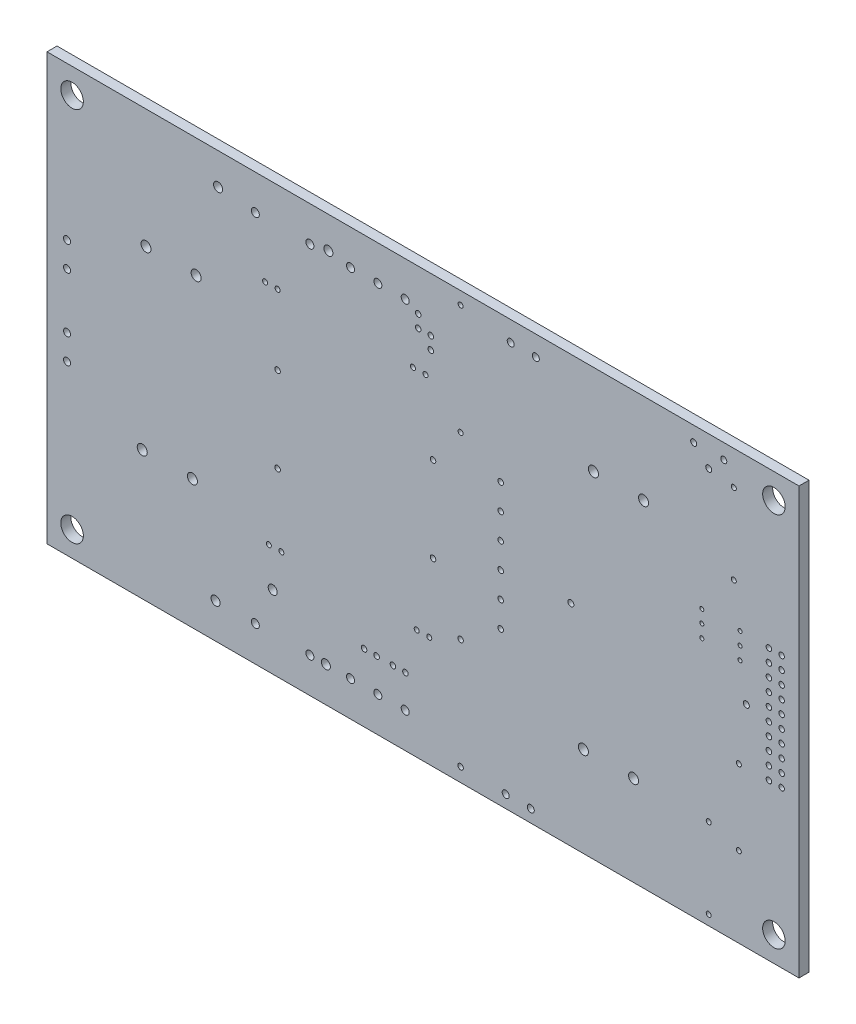
SolidWorks part; units mm, degrees
ref_plane "Спереди" through (0, 0, 0) normal (0, 0, 1) x (1, 0, 0)
ref_plane "Сверху" through (0, 0, 0) normal (0, 1, 0) x (1, 0, 0)
ref_plane "Справа" through (0, 0, 0) normal (1, 0, 0) x (0, 0, -1)
sketch "Эскиз1" plane through (0, 0, 0) normal (0, 0, 1) x (1, 0, 0)
  line L0 (-22.6071, 0) -> (23.7373, 0) construction
  line L1 (-75, -42.5) -> (75, -42.5)
  line L2 (-75, -42.5) -> (-75, 42.5)
  line L3 (-75, 42.5) -> (75, 42.5)
  line L4 (75, -42.5) -> (75, 42.5)
  line L5 (0, 0) -> (0, 31.6453) construction
  circle A0 centre (-70, -37.5) radius 2.25
  circle A1 centre (70, -37.5) radius 2.25
  circle A2 centre (70, 37.5) radius 2.25
  circle A3 centre (-70, 37.5) radius 2.25
  dimension "D3" = 4.5
  dimension "D1" = 150
  dimension "D2" = 85
  dimension "D4" = 5
  dimension "D5" = 5
extrude "Вытянуть1" add sketch "Эскиз1" along normal blind 2
sketch "Эскиз2" plane through (0, 0, 2) normal (0, 0, 1) x (1, 0, 0)
  line L0 (-75, 42.5) -> (-75, -42.5) construction
  line L1 (-75, -42.5) -> (75, -42.5) construction
  line L2 (-33.45, 35.5) -> (-22.55, 35.5) construction
  line L3 (-14.45, -35.5) -> (-3.55, -35.5) construction
  line L4 (69, 11.5) -> (71.54, 11.5) construction
  line L5 (15.5, -11.95) -> (48.2663, -11.95) construction
  line L6 (15.5, -11.95) -> (27.9466, 0.4966) construction
  line L14 (63, -26.5) -> (63, -11.5) construction
  line L15 (-14.45, 35.5) -> (-3.55, 35.5) construction
  line L16 (-33.45, -35.5) -> (-22.55, -35.5) construction
  line L18 (15.5, -22.58) -> (15.5, -11.95) construction
  circle A0 centre (69, 11.5) radius 0.55
  circle A1 centre (71.54, 11.5) radius 0.55
  circle A2 centre (69, 8.96) radius 0.55
  circle A3 centre (71.54, 8.96) radius 0.55
  circle A4 centre (69, 6.42) radius 0.55
  circle A5 centre (71.54, 6.42) radius 0.55
  circle A6 centre (69, 3.88) radius 0.55
  circle A7 centre (71.54, 3.88) radius 0.55
  circle A8 centre (69, 1.34) radius 0.55
  circle A9 centre (71.54, 1.34) radius 0.55
  circle A10 centre (69, -1.2) radius 0.55
  circle A11 centre (71.54, -1.2) radius 0.55
  circle A12 centre (69, -3.74) radius 0.55
  circle A13 centre (71.54, -3.74) radius 0.55
  circle A14 centre (69, -6.28) radius 0.55
  circle A15 centre (71.54, -6.28) radius 0.55
  circle A16 centre (69, -8.82) radius 0.55
  circle A17 centre (71.54, -8.82) radius 0.55
  circle A18 centre (69, -11.36) radius 0.55
  circle A19 centre (71.54, -11.36) radius 0.55
  circle A20 centre (63, -26.5) radius 0.5
  circle A21 centre (63, -11.5) radius 0.5
  circle A22 centre (-14.45, 35.5) radius 0.8
  circle A23 centre (-9, 35.5) radius 0.8
  circle A24 centre (-3.55, 35.5) radius 0.8
  circle A25 centre (-33.45, 35.5) radius 0.8
  circle A27 centre (-22.55, 35.5) radius 0.8
  circle A28 centre (-33.45, -35.5) radius 0.8
  circle A30 centre (-22.55, -35.5) radius 0.8
  circle A31 centre (-14.45, -35.5) radius 0.8
  circle A32 centre (-9, -35.5) radius 0.8
  circle A33 centre (-3.55, -35.5) radius 0.8
  circle A37 centre (15.5, 13.45) radius 0.55
  circle A38 centre (15.5, 8.37) radius 0.55
  circle A39 centre (15.5, -1.79) radius 0.55
  circle A40 centre (15.5, 3.29) radius 0.55
  circle A41 centre (15.5, -6.87) radius 0.55
  circle A45 centre (15.5, -11.95) radius 0.55
  dimension "D3" = 1.1
  dimension "D4" = 2.54
  dimension "D7" = 1
  dimension "D8" = 138
  dimension "D9" = 60.55
  dimension "D10" = 10.9
  dimension "D11" = 1.1
  dimension "D12" = 78
  dimension "D13" = 1.6
  dimension "D19" = 1.6
  dimension "D20" = 5.45
  dimension "D14" = 10.9
  dimension "D26" = 10.9
  dimension "D30" = 5.08
  dimension "D32" = 30.55
  dimension "D6" = 15
  dimension "D33" = 5.08
  dimension "D34" = 5.08
  dimension "D36" = 5.08
  dimension "D42" = 1.6
  dimension "D24" = 54
  dimension "D35" = 5.08
  dimension "D1" = 144
  dimension "D5" = 16
  dimension "D15" = 41.55
  dimension "D16" = 78
  dimension "D17" = 7
  dimension "D18" = 7
  dimension "D21" = 41.55
  dimension "D22" = 60.55
  dimension "D25" = 45
  dimension "D31" = 90.5
extrude "Вырез-Вытянуть1" cut sketch "Эскиз2" against normal blind 2
sketch "Эскиз3" plane through (0, 0, 2) normal (0, 0, 1) x (1, 0, 0)
  line L0 (-75, -42.5) -> (75, -42.5) construction
  line L1 (-75, 42.5) -> (-75, -42.5) construction
  line L2 (-55.25, 18.75) -> (-45.25, 18.75) construction
  line L6 (16.5, -40) -> (21.5, -40) construction
  line L7 (-71, 7) -> (-71, 12) construction
  line L8 (-71, -9) -> (-71, -4) construction
  line L9 (-75, -42.5) -> (75, -42.5) construction
  line L12 (57, -40.5) -> (57, -24.5) construction
  line L14 (47.25, 45) -> (47.25, 55) construction
  line L16 (34, 24.5) -> (44, 24.5) construction
  line L17 (32, -24.5) -> (42, -24.5) construction
  line L18 (-56, -16.75) -> (-46, -16.75) construction
  line L19 (62, 19.75) -> (62, 35.75) construction
  line L20 (63.24, 11.58) -> (63.24, 6.5) construction
  line L21 (55.62, 6.5) -> (55.62, 12.7862) construction
  line L22 (55.62, 6.5) -> (63.24, 6.5) construction
  line L23 (54, 39.5) -> (60, 39.5) construction
  line L24 (17.5, 38.5) -> (22.5, 38.5) construction
  line L25 (29.5, -0.5) -> (64.5, -0.5) construction
  circle A0 centre (-55.25, 18.75) radius 1
  circle A1 centre (-45.25, 18.75) radius 1
  circle A2 centre (-56, -16.75) radius 1
  circle A3 centre (-46, -16.75) radius 1
  circle A4 centre (54, 39.5) radius 0.6
  circle A5 centre (60, 39.5) radius 0.6
  circle A10 centre (16.5, -40) radius 0.7
  circle A12 centre (21.5, -40) radius 0.7
  circle A13 centre (-71, 7) radius 0.7
  circle A14 centre (-71, 12) radius 0.7
  circle A15 centre (-71, -9) radius 0.7
  circle A16 centre (-71, -4) radius 0.7
  circle A20 centre (57, -40.5) radius 0.5
  circle A21 centre (57, -24.5) radius 0.5
  circle A28 centre (34, 24.5) radius 1
  circle A29 centre (44, 24.5) radius 1
  circle A30 centre (32, -24.5) radius 1
  circle A31 centre (42, -24.5) radius 1
  circle A34 centre (57, 36.5) radius 0.6
  circle A35 centre (17.5, 38.5) radius 0.7
  circle A36 centre (62, 19.75) radius 0.5
  circle A37 centre (62, 35.75) radius 0.5
  circle A38 centre (63.24, 11.58) radius 0.4
  circle A39 centre (63.24, 6.5) radius 0.4
  circle A40 centre (55.62, 9.04) radius 0.4
  circle A41 centre (63.24, 9.04) radius 0.4
  circle A42 centre (55.62, 6.5) radius 0.4
  circle A43 centre (55.62, 11.58) radius 0.4
  circle A44 centre (22.5, 38.5) radius 0.7
  circle A45 centre (64.5, -0.5) radius 0.6
  circle A46 centre (29.5, -0.5) radius 0.6
  dimension "D16" = 91.5
  dimension "D17" = 5
  dimension "D18" = 49.5
  dimension "D22" = 1.2
  dimension "D23" = 1.2
  dimension "D28" = 1
  dimension "D44" = 10
  dimension "D14" = 5
  dimension "D15" = 2.5
  dimension "D30" = 16
  dimension "D35" = 10
  dimension "D20" = 1.4
  dimension "D50" = 1.4
  dimension "D56" = 19.75
  dimension "D58" = 25.75
  dimension "D59" = 16
  dimension "D63" = 7.62
  dimension "D64" = 2.54
  dimension "D65" = 5.08
  dimension "D67" = 130.62
  dimension "D70" = 6
  dimension "D72" = 6
  dimension "D76" = 5
  dimension "D77" = 1.4
  dimension "D78" = 35
  dimension "D19" = 4
  dimension "D21" = 5
  dimension "D29" = 2
  dimension "D31" = 132
  dimension "D34" = 10
  dimension "D38" = 122.25
  dimension "D45" = 67
  dimension "D46" = 109
  dimension "D47" = 10
  dimension "D48" = 18
  dimension "D49" = 107
  dimension "D51" = 4
  dimension "D52" = 33.5
  dimension "D57" = 61.25
  dimension "D60" = 137
  dimension "D61" = 62.25
  dimension "D62" = 5.08
  dimension "D66" = 49
  dimension "D68" = 19
  dimension "D69" = 3
  dimension "D71" = 82
  dimension "D73" = 129
  dimension "D74" = 81
  dimension "D75" = 92.5
  dimension "D79" = 42
  dimension "D80" = 104.5
extrude "Вырез-Вытянуть2" cut sketch "Эскиз3" against normal blind 10
sketch "Эскиз4" plane through (0, 0, 2) normal (0, 0, 1) x (1, 0, 0)
  line L0 (-41.37, -35.5) -> (-19.37, -35.5) construction
  line L1 (-75, 42.5) -> (-75, -42.5) construction
  line L2 (-75, -42.5) -> (75, -42.5) construction
  line L3 (-40.87, 36.2) -> (-18.87, 36.2) construction
  line L4 (-31.5, 24.5) -> (0.5, 24.5) construction
  line L5 (-0.95, 31.75) -> (1.55, 31.75) construction
  line L6 (7.5, -39.75) -> (7.5, -17.75) construction
  line L7 (-0.95, 31.75) -> (-0.95, 34.25) construction
  line L8 (-11.75, -29) -> (-9.25, -29) construction
  line L9 (7.5, 18) -> (7.5, 40) construction
  line L11 (-29, 10.5) -> (2, 10.5) construction
  line L15 (-29, -6.5) -> (2, -6.5) construction
  line L16 (-30.75, -20.5) -> (1.25, -20.5) construction
  circle A0 centre (-41.37, -35.5) radius 0.9
  circle A1 centre (-40.87, 36.2) radius 0.9
  circle A2 centre (-31.5, 24.5) radius 0.5
  circle A3 centre (-19.37, -35.5) radius 0.9
  circle A4 centre (-6, -29) radius 0.55
  circle A5 centre (-18.87, 36.2) radius 0.9
  circle A6 centre (0.5, 24.5) radius 0.5
  circle A7 centre (-29, 24.5) radius 0.5
  circle A8 centre (-0.95, 31.75) radius 0.55
  circle A9 centre (1.55, 31.75) radius 0.55
  circle A10 centre (-2, 24.5) radius 0.5
  circle A11 centre (7.5, -39.75) radius 0.55
  circle A12 centre (7.5, -17.75) radius 0.55
  circle A13 centre (-29.979, -27.918) radius 0.9
  circle A14 centre (-11.75, -29) radius 0.55
  circle A15 centre (7.5, 18) radius 0.5
  circle A16 centre (7.5, 40) radius 0.5
  circle A17 centre (-9.25, -29) radius 0.55
  circle A18 centre (-3.5, -29) radius 0.55
  circle A19 centre (-29, 10.5) radius 0.55
  circle A20 centre (2, 10.5) radius 0.55
  circle A21 centre (-0.95, 34.25) radius 0.55
  circle A22 centre (1.55, 29.25) radius 0.55
  circle A40 centre (-29, -6.5) radius 0.55
  circle A41 centre (2, -6.5) radius 0.55
  circle A42 centre (-30.75, -20.5) radius 0.5
  circle A43 centre (1.25, -20.5) radius 0.5
  circle A44 centre (-28.25, -20.5) radius 0.5
  circle A45 centre (-1.25, -20.5) radius 0.5
  dimension "D5" = 2.5
  dimension "D9" = 7
  dimension "D10" = 32
  dimension "D12" = 67
  dimension "D15" = 34.13
  dimension "D19" = 82.5
  dimension "D24" = 2.5
  dimension "D25" = 31
  dimension "D26" = 1.1
  dimension "D29" = 1
  dimension "D31" = 73.5
  dimension "D37" = 63.25
  dimension "D38" = 2.5
  dimension "D39" = 46
  dimension "D40" = 53
  dimension "D41" = 69
  dimension "D42" = 13.5
  dimension "D71" = 27
  dimension "D72" = 32
  dimension "D73" = 2.5
  dimension "D74" = 44.25
  dimension "D44" = 2.5
  dimension "D13" = 22
  dimension "D18" = 2.75
  dimension "D20" = 22
  dimension "D22" = 82.5
  dimension "D23" = 60.5
  dimension "D27" = 36
  dimension "D28" = 46
  dimension "D30" = 1.1
  dimension "D14" = 22
  dimension "D16" = 78.7
  dimension "D17" = 33.63
  dimension "D34" = 74.25
  dimension "D35" = 2.5
  dimension "D36" = 13.5
  dimension "D21" = 22
  dimension "D33" = 1.1
  dimension "D8" = 1.8
  dimension "D43" = 2.5
  dimension "D4" = 27
  dimension "D11" = 43.5
  dimension "D32" = 31
  dimension "D67" = 22
extrude "Вырез-Вытянуть3" cut sketch "Эскиз4" against normal blind 10
